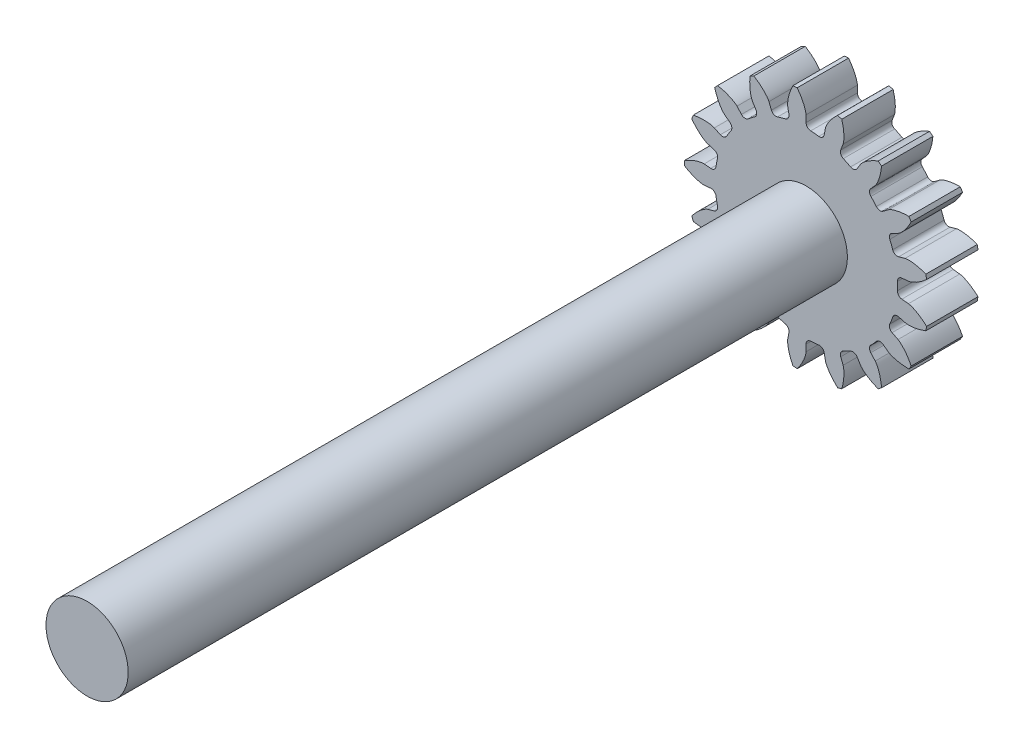
SolidWorks part; units mm, degrees
ref_plane "Front Plane" through (0, 0, 0) normal (0, 0, 1) x (1, 0, 0)
ref_plane "Top Plane" through (0, 0, 0) normal (0, 1, 0) x (1, 0, 0)
ref_plane "Right Plane" through (0, 0, 0) normal (1, 0, 0) x (0, 0, -1)
ref_axis "Gear Axis" through (0, 0, -0.2501) along (0, 0, 1)
sketch "Blank Sketch" plane through (0, 0, 0) normal (0, 0, 1) x (1, 0, 0)
  circle A0 centre (0, 0) radius 11.875
  dimension "OD" = 23.75
extrude "Blank" add sketch "Blank Sketch" along normal blind 5
sketch "Tooth Space Sketch" plane through (0, 0, 0) normal (0, 0, 1) x (1, 0, 0)
  line L0 (9.9391, 0.9485) -> (9.2957, 0.8871)
  line L1 (9.9391, -0.9485) -> (9.2957, -0.8871)
  line L2 (12.7424, 3.1457) -> (12.7424, -3.1457)
  arc A0 (9.2957, 0.8871) -> (8.8663, 0.3932) centre (9.3408, 0.4142) ccw
  arc A1 (8.8663, -0.3932) -> (9.2957, -0.8871) centre (9.3408, -0.4142) ccw
  arc A2 (8.8663, -0.3932) -> (8.8663, 0.3932) centre (0, 0) ccw
  spline S0 degree 4 poles (9.9391, 0.9485) (9.9444, 0.9491) (9.9594, 0.9511) (9.9875, 0.9561) (10.033, 0.9658) (10.0906, 0.9807) (10.1644, 1.0027) (10.2505, 1.0321) (10.344, 1.0681) (10.4445, 1.1112) (10.5435, 1.1577) (10.6412, 1.2072) (10.7373, 1.2593) (10.8523, 1.3258) (10.9883, 1.4101) (11.1441, 1.5151) (11.3169, 1.6419) (11.4885, 1.7791) (11.6537, 1.9206) (11.816, 2.0708) (11.9698, 2.2212) (12.1246, 2.3846) (12.2649, 2.5391) (12.4162, 2.7198) (12.5367, 2.8679) (12.6891, 3.071) (12.7772, 3.1933) (12.878, 3.3391) (12.9216, 3.4052) (12.9484, 3.4459) knots 0 0 0 0 0 0.005377 0.015084 0.028532 0.04661 0.064855 0.092111 0.119476 0.146842 0.174209 0.201575 0.228941 0.256307 0.307035 0.361767 0.4165 0.471232 0.525964 0.580697 0.635429 0.690161 0.744894 0.799626 0.854358 0.909091 0.954545 1 1 1 1 1 construction
  spline S1 degree 4 poles (9.9391, 0.9485) (9.9444, 0.9491) (9.9594, 0.9511) (9.9875, 0.9561) (10.033, 0.9658) (10.0906, 0.9807) (10.1644, 1.0027) (10.2505, 1.0321) (10.344, 1.0681) (10.4445, 1.1112) (10.5435, 1.1577) (10.6412, 1.2072) (10.7373, 1.2593) (10.8523, 1.3258) (10.9883, 1.4101) (11.1441, 1.5151) (11.3169, 1.6419) (11.4885, 1.7791) (11.6537, 1.9206) (11.816, 2.0708) (11.9698, 2.2212) (12.1246, 2.3846) (12.2649, 2.5391) (12.4162, 2.7198) (12.5367, 2.8679) (12.6561, 3.027) (12.7135, 3.1053) (12.7424, 3.1457) knots 0 0 0 0 0 0.005377 0.015084 0.028532 0.04661 0.064855 0.092111 0.119476 0.146842 0.174209 0.201575 0.228941 0.256307 0.307035 0.361767 0.4165 0.471232 0.525964 0.580697 0.635429 0.690161 0.744894 0.799626 0.854358 0.909091 0.909091 0.909091 0.909091 0.909091
  spline S2 degree 4 poles (9.9391, -0.9485) (9.9444, -0.9491) (9.9594, -0.9511) (9.9875, -0.9561) (10.033, -0.9658) (10.0906, -0.9807) (10.1644, -1.0027) (10.2505, -1.0321) (10.344, -1.0681) (10.4445, -1.1112) (10.5435, -1.1577) (10.6412, -1.2072) (10.7373, -1.2593) (10.8523, -1.3258) (10.9883, -1.4101) (11.1441, -1.5151) (11.3169, -1.6419) (11.4885, -1.7791) (11.6537, -1.9206) (11.816, -2.0708) (11.9698, -2.2212) (12.1246, -2.3846) (12.2649, -2.5391) (12.4162, -2.7198) (12.5367, -2.8679) (12.6891, -3.071) (12.7772, -3.1933) (12.878, -3.3391) (12.9216, -3.4052) (12.9484, -3.4459) knots 0 0 0 0 0 0.005377 0.015084 0.028532 0.04661 0.064855 0.092111 0.119476 0.146842 0.174209 0.201575 0.228941 0.256307 0.307035 0.361767 0.4165 0.471232 0.525964 0.580697 0.635429 0.690161 0.744894 0.799626 0.854358 0.909091 0.954545 1 1 1 1 1 construction
  spline S3 degree 4 poles (9.9391, -0.9485) (9.9444, -0.9491) (9.9594, -0.9511) (9.9875, -0.9561) (10.033, -0.9658) (10.0906, -0.9807) (10.1644, -1.0027) (10.2505, -1.0321) (10.344, -1.0681) (10.4445, -1.1112) (10.5435, -1.1577) (10.6412, -1.2072) (10.7373, -1.2593) (10.8523, -1.3258) (10.9883, -1.4101) (11.1441, -1.5151) (11.3169, -1.6419) (11.4885, -1.7791) (11.6537, -1.9206) (11.816, -2.0708) (11.9698, -2.2212) (12.1246, -2.3846) (12.2649, -2.5391) (12.4162, -2.7198) (12.5367, -2.8679) (12.6561, -3.027) (12.7135, -3.1053) (12.7424, -3.1457) knots 0 0 0 0 0 0.005377 0.015084 0.028532 0.04661 0.064855 0.092111 0.119476 0.146842 0.174209 0.201575 0.228941 0.256307 0.307035 0.361767 0.4165 0.471232 0.525964 0.580697 0.635429 0.690161 0.744894 0.799626 0.854358 0.909091 0.909091 0.909091 0.909091 0.909091
  dimension "Root" = 8.875
  dimension "Fillet" = 0.475
extrude "Tooth Space" cut sketch "Tooth Space Sketch" against normal through all both and the other way through all both
pattern_circular "Teeth" count 17 over 360 about axis through (0, 0, -0.2501) along (0, 0, 1) of "Tooth Space"
sketch "Bore Sketch" plane through (0, 0, 0) normal (0, 0, 1) x (1, 0, 0)
  circle A0 centre (0, 0) radius 4
  dimension "Bore" = 8
extrude "Bore" cut sketch "Bore Sketch" against normal through all both and the other way through all both
sketch "Sketch1" plane through (0, 0, 0) normal (0, 0, -1) x (-1, 0, 0)
  circle A1 centre (0, 0) radius 4
  circle A2 centre (0, 0) radius 4
  dimension "D1" = 0
extrude "Boss-Extrude1" add sketch "Sketch1" against normal blind 75
equation "\"No. of Teeth\"= 17"
equation "\"Module\"= 1.25"
equation "\"Bore Diameter\"= 8"
equation "\"Pressure Angle\"= 20"
equation "\"Outer Diameter\"= ( \"No. of Teeth\" + 2 ) * \"Module\""
equation "\"Pitch Diameter\"= \"No. of Teeth\" * \"Module\""
equation "\"Backlash\"= 0.3 * \"Module\""
equation "\"Arc Length\"= ( ( \"Module\" * pi ) / 2 + \"Backlash\" )"
equation "\"Fillet Radius\"= 0.38 * \"Module\""
equation "\"Tooth Depth\"= IIF ( \"Module\" <= 1.25 , \"Module\" * 2.4 , \"Module\" * 2.25 )"
equation "\"Face Width\"= 5"
equation "\"Root Diameter\"= \"Outer Diameter\" - 2 * \"Tooth Depth\""
equation "\"Base Diameter\"= \"Pitch Diameter\" * cos ( \"Pressure Angle\" )"
equation "\"Base Radius\"= \"Base Diameter\" / 2"
equation "\"Tooth Thickness\"= \"Module\" * pi - \"Arc Length\""
equation "\"Half Space Angle\"= ( \"Arc Length\" / \"Pitch Diameter\" ) * 180 / pi"
equation "\"Involute Fn\"= tan ( \"Pressure Angle\" ) - \"Pressure Angle\" * pi / 180"
equation "\"Flank Offset\"= \"Arc Length\" / \"Pitch Diameter\" - \"Involute Fn\""
equation "\"Tip Cap Diameter\"= \"Outer Diameter\" + 2 * \"Module\""
equation "\"Flank Start Diameter\"= IIF ( \"Base Diameter\" >= ( \"Root Diameter\" + 3 * \"Fillet Radius\" ) , \"Base Diameter\" , \"Root Diameter\" + 3 * \"Fillet Radius\" )"
equation "\"Involute t1\"= ( abs ( ( \"Flank Start Diameter\" / \"Base Diameter\" ) ^ 2 - 1 ) ) ^ 0.5"
equation "\"Involute t2\"= ( abs ( ( \"Tip Cap Diameter\" / \"Base Diameter\" ) ^ 2 - 1 ) ) ^ 0.5"
equation "\"Flank Arc Radius\"= ( \"Pitch Diameter\" / 2 ) * sin ( \"Pressure Angle\" )"
equation "\"Flank Centre Angle\"= \"Half Space Angle\" + \"Pressure Angle\""
equation "\"OD@Blank Sketch\"= \"Outer Diameter\""
equation "\"Width@Blank\"= \"Face Width\""
equation "\"Root@Tooth Space Sketch\"= \"Root Diameter\" / 2"
equation "\"Fillet@Tooth Space Sketch\"= \"Fillet Radius\""
equation "\"Count@Teeth\"= \"No. of Teeth\""
equation "\"Bore@Bore Sketch\"= \"Bore Diameter\""
